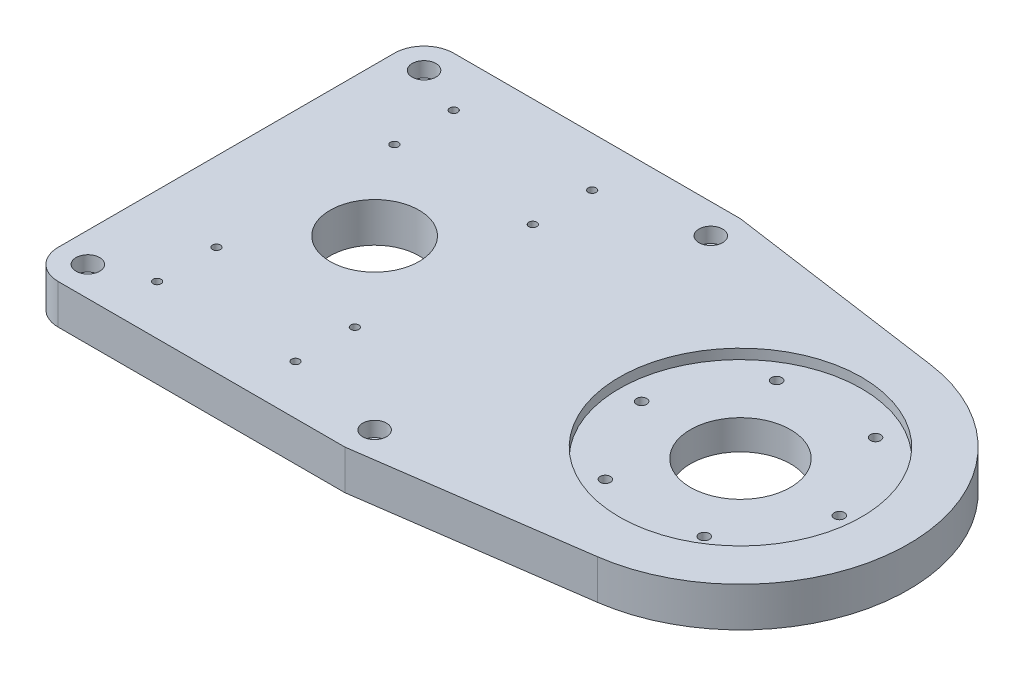
SolidWorks part; units mm, degrees
material "ASTM A36 Steel"
ref_plane "Front Plane" through (0, 0, 0) normal (0, 0, 1) x (1, 0, 0)
ref_plane "Top Plane" through (0, 0, 0) normal (0, 1, 0) x (1, 0, 0)
ref_plane "Right Plane" through (0, 0, 0) normal (1, 0, 0) x (0, 0, -1)
sketch "Sketch1" plane through (0, 0, 0) normal (0, 1, 0) x (1, 0, 0)
  line L0 (0, 0) -> (-50000, 0) construction
  line L1 (-95.25, 107.95) -> (-95.25, -107.95)
  line L2 (-76.2, 127) -> (107.95, 127)
  line L3 (-76.2, -127) -> (107.95, -127)
  line L4 (107.95, 127) -> (250.0773, 106.8848)
  line L5 (107.95, -127) -> (250.0773, -106.8848)
  circle A0 centre (0, 0) radius 28.575
  arc A2 (-95.25, -107.95) -> (-76.2, -127) centre (-76.2, -107.95) ccw
  arc A3 (-95.25, 107.95) -> (-76.2, 127) centre (-76.2, 107.95) cw
  arc A4 (250.0773, -106.8848) -> (250.0773, 106.8848) centre (234.95, 0) ccw
  circle A5 centre (234.95, 0) radius 32.1437
  point P3 (234.95, 0)
  point P7 (-95.25, 0)
  point P11 (-95.25, 0)
  point P16 (-95.25, -127)
  point P19 (-95.25, 127)
  dimension "D1" = 57.15
  dimension "D5" = 19.05
  dimension "D7" = 107.95
  dimension "D8" = 64.2874
  dimension "D2" = 95.25
  dimension "D3" = 254
  dimension "D4" = 203.2
  dimension "D6" = 330.2
extrude "Boss-Extrude1" add sketch "Sketch1" along normal blind 25.4
hole_wizard "CBORE for #00 Binding Head Machine Screw1" positions "3DSketch1" profile "Sketch3" counterbore size "#00" standard "ANSI Inch" end condition through all
sketch3d "3DSketch1"
  line L0 (-76.2, 25.4, -107.95) -> (-76.2, 0, -107.95) construction
  line L1 (-76.2, 25.4, 107.95) -> (-76.2, 0, 107.95) construction
  line L2 (-95.25, 25.4, -107.95) -> (-95.25, 25.4, 107.95) construction
  point P0 (-76.2, 25.4, -107.95)
  point P4 (-76.2, 25.4, 107.95)
  point P9 (107.95, 25.4, -107.95)
  point P11 (107.95, 25.4, 107.95)
  point P13 (0, 0, 0)
  point P14 (0, 0, 0)
  point P15 (0, 0, 0)
  point P16 (0, 0, 0)
  dimension "D1" = 203.2
sketch "Sketch3" plane through (-76.2, 25.4, -107.95) normal (1, 0, 0) x (0, 0, 1)
  line L0 (0, 0) -> (0, 25.4)
  line L1 (0, 25.4) -> (5.08, 25.4)
  line L3 (5.08, 25.4) -> (5.08, 9.652)
  line L4 (5.08, 9.652) -> (7.62, 9.652)
  line L5 (7.62, 9.652) -> (7.62, 0)
  line L7 (7.62, 0) -> (0, 0)
  line L11 (0, -6.35) -> (0, 107.95) construction
  dimension "Thru Hole Dia." = 10.16
  dimension "Thru Hole Depth" = 25.4
  dimension "C'Bore Dia." = 15.24
  dimension "C'Bore Depth" = 9.652
hole_wizard "1/4-20 Tapped Hole1" positions "3DSketch2" profile "Sketch4" tap size "1/4-20" standard "ANSI Inch"
sketch3d "3DSketch2"
  line L0 (-95.25, 25.4, -107.95) -> (-95.25, 25.4, 107.95) construction
  line L1 (0, 25.4, 0) -> (-95.25, 25.4, 0) construction
  line L2 (0, 25.4, 0) -> (0, 0, 0) construction
  point P0 (-44.45, 25.4, -95.25)
  point P2 (44.45, 25.4, -95.25)
  point P4 (44.45, 25.4, -57.15)
  point P6 (-44.45, 25.4, -57.15)
  point P8 (-44.45, 25.4, 57.15)
  point P10 (44.45, 25.4, 57.15)
  point P12 (44.45, 25.4, 95.25)
  point P14 (-44.45, 25.4, 95.25)
  dimension "D1" = 50.8
  dimension "D2" = 139.7
  dimension "D3" = 57.15
  dimension "D4" = 57.15
  dimension "D5" = 95.25
  dimension "D6" = 95.25
sketch "Sketch4" plane through (-44.45, 25.4, -95.25) normal (1, 0, 0) x (0, 0, 1)
  line L0 (0, 0) -> (0, 19.05)
  line L1 (0, 19.05) -> (2.5527, 17.5162)
  line L2 (2.5527, 17.5162) -> (2.5527, 0)
  line L5 (2.5527, 0) -> (0, 0)
  line L10 (0, 19.05) -> (-2.5527, 17.5162) construction
  line L11 (0, -6.35) -> (0, 107.95) construction
  dimension "Tap Drill Dia." = 5.1054
  dimension "Tap Drill Depth" = 19.05
  dimension "Drill Angle" = 118
cosmetic thread "Hole Thread9" parameters "D1"=12.7, "D2"=6.35
cosmetic thread "Hole Thread10" parameters "D1"=12.7, "D2"=6.35
cosmetic thread "Hole Thread11" parameters "D1"=12.7, "D2"=6.35
cosmetic thread "Hole Thread12" parameters "D1"=12.7, "D2"=6.35
cosmetic thread "Hole Thread13" parameters "D1"=12.7, "D2"=6.35
cosmetic thread "Hole Thread14" parameters "D1"=12.7, "D2"=6.35
cosmetic thread "Hole Thread15" parameters "D1"=12.7, "D2"=6.35
cosmetic thread "Hole Thread16" parameters "D1"=12.7, "D2"=6.35
sketch "Sketch5" plane through (0, 25.4, 0) normal (0, 1, 0) x (1, 0, 0)
  circle A0 centre (234.95, 0) radius 77.7875
  circle A2 centre (234.95, 0) radius 32.1437 construction
  dimension "D1" = 155.575
extrude "Cut-Extrude1" cut sketch "Sketch5" against normal blind 6.35
hole_wizard "5/16-18 Tapped Hole1" positions "3DSketch3" profile "Sketch7" tap size "5/16-18" standard "ANSI Inch" end condition through all
sketch3d "3DSketch3"
  line L0 (234.95, 19.05, 0) -> (234.95, 0, 0) construction
  circle A1 centre (234.95, 19.05, 0) radius 63.5 construction
  circle A3 centre (234.95, 19.05, 0) radius 77.7875 construction
  point P0 (298.45, 19.05, 0)
  point P9 (234.95, 82.55, 0)
  point P13 (0, 0, 0)
  point P19 (234.95, 96.8375, 0)
  point P20 (0, 0, 0)
  point P21 (0, 0, 0)
  dimension "D1" = 127
sketch "Sketch7" plane through (298.45, 19.05, 0) normal (1, 0, 0) x (0, 0, 1)
  line L0 (0, 0) -> (0, 19.05)
  line L1 (0, 19.05) -> (3.302, 19.05)
  line L2 (3.302, 19.05) -> (3.302, 0)
  line L5 (3.302, 0) -> (0, 0)
  line L11 (0, -6.35) -> (0, 107.95) construction
  dimension "Thru Tap Drill Dia." = 6.604
  dimension "Thru Tap Drill Depth" = 19.05
cosmetic thread "Hole Thread17" parameters "D2"=7.9375
pattern_circular "CirPattern1" count 6 over 360 about axis through (234.95, 0, 0) along (0, 1, 0) of "5/16-18 Tapped Hole1"
cosmetic thread "Hole Thread18" parameters "D2"=7.9375
cosmetic thread "Hole Thread19" parameters "D2"=7.9375
cosmetic thread "Hole Thread20" parameters "D2"=7.9375
cosmetic thread "Hole Thread21" parameters "D2"=7.9375
cosmetic thread "Hole Thread22" parameters "D2"=7.9375
